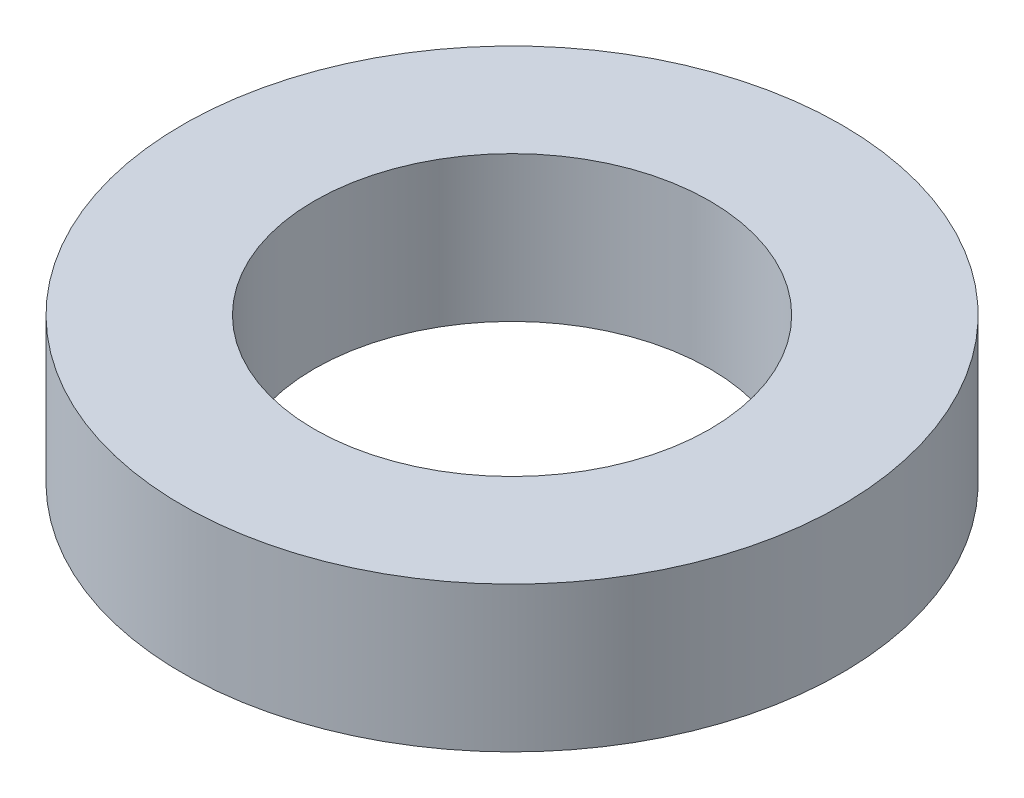
SolidWorks part; units mm, degrees
ref_plane "Front Plane" through (0, 0, 0) normal (0, 0, 1) x (1, 0, 0)
ref_plane "Top Plane" through (0, 0, 0) normal (0, 1, 0) x (1, 0, 0)
ref_plane "Right Plane" through (0, 0, 0) normal (1, 0, 0) x (0, 0, -1)
sketch "Sketch1" plane through (0, 0, 0) normal (0, 1, 0) x (1, 0, 0)
  circle A0 centre (0, 0) radius 7.9375
  circle A1 centre (0, 0) radius 4.7625
extrude "Boss-Extrude1" add sketch "Sketch1" along normal blind 3.5
